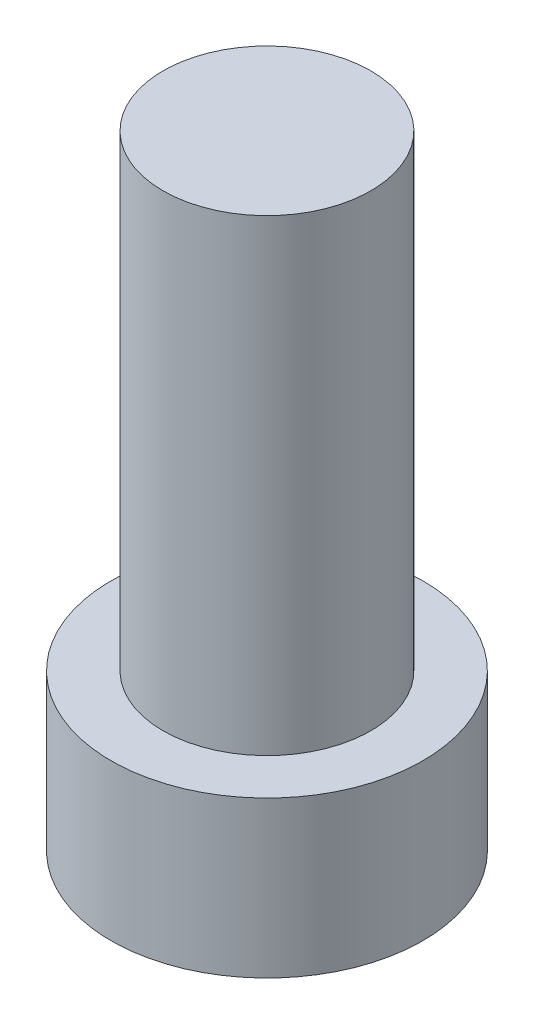
SolidWorks part; units mm, degrees
material "3003-O"
ref_plane "Front Plane" through (0, 0, 0) normal (0, 0, 1) x (1, 0, 0)
ref_plane "Top Plane" through (0, 0, 0) normal (0, 1, 0) x (1, 0, 0)
ref_plane "Right Plane" through (0, 0, 0) normal (1, 0, 0) x (0, 0, -1)
sketch "Sketch1" plane through (0, 0, 0) normal (0, 0, 1) x (1, 0, 0)
  line L0 (0, 0) -> (4.7625, 0)
  line L1 (4.7625, 0) -> (4.7625, 4.7625)
  line L2 (4.7625, 4.7625) -> (3.175, 4.7625)
  line L3 (3.175, 4.7625) -> (3.175, 19.05)
  line L4 (3.175, 19.05) -> (0, 19.05)
  line L5 (0, 19.05) -> (0, 0)
  line L6 (0, 0) -> (0, 12.1374) construction
  dimension "D1" = 6.35
  dimension "D2" = 19.05
  dimension "D3" = 4.7625
  dimension "D4" = 1.5875
revolve "Revolve1" add sketch "Sketch1" angle 360 about L6
